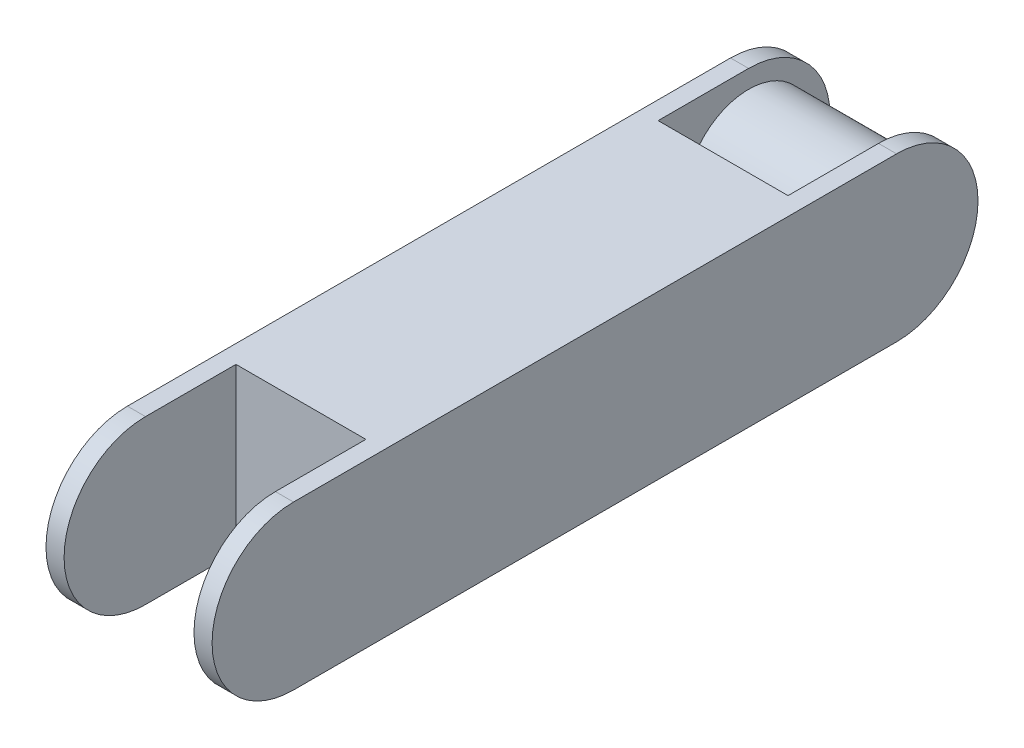
SolidWorks part; units mm, degrees
ref_plane "Piano frontale" through (0, 0, 0) normal (0, 0, 1) x (1, 0, 0)
ref_plane "Piano superiore" through (0, 0, 0) normal (0, 1, 0) x (1, 0, 0)
ref_plane "Piano destro" through (0, 0, 0) normal (1, 0, 0) x (0, 0, -1)
sketch "Schizzo1" plane through (0, 0, 0) normal (1, 0, 0) x (0, 0, -1)
  circle A0 centre (0, 0) radius 10.5
  dimension "D1" = 21
extrude "Estrusione-Estrusione1" add sketch "Schizzo1" along normal mid plane 21.54
ref_plane "Piano1" through (0, 0, 50) normal (0, 0, 1) x (1, 0, 0)
sketch "Schizzo3" plane through (0, 0, 0) normal (1, 0, 0) x (0, 0, -1)
  line L0 (-50, -14.5808) -> (-50, 15.0229) construction
  line L1 (-100, 13.5) -> (0, 13.5)
  line L2 (-100, -13.5) -> (0, -13.5)
  arc A1 (-100, -13.5) -> (-100, 13.5) centre (-100, 0) cw
  circle A2 centre (0, 0) radius 13.5
  arc A3 (0, -13.5) -> (0, 13.5) centre (0, 0) ccw
  dimension "D1" = 50
  dimension "D2" = 3
extrude "Estrusione-Estrusione2" add sketch "Schizzo3" along normal blind 3 from surface at 10.77 starting at face at (10.77, 0, -10.5)
mirror "Specchia4" about plane through (0, 0, 0) normal (1, 0, 0) of "Estrusione-Estrusione2"
sketch "Schizzo4" plane through (13.77, 0, 0) normal (1, 0, 0) x (0, 0, -1)
  line L0 (0, -13.5) -> (-100, -13.5) construction
  line L1 (-15, -13.5) -> (-85, -13.5)
  line L2 (-15, -13.5) -> (-15, 13.5)
  line L3 (-15, 13.5) -> (-85, 13.5)
  line L4 (-85, -13.5) -> (-85, 13.5)
  line L5 (-100, 13.5) -> (0, 13.5) construction
  arc A0 (-100, 13.5) -> (-100, -13.5) centre (-100, 0) ccw construction
  dimension "D1" = 15
  dimension "D2" = 15
extrude "Estrusione-Estrusione3" add sketch "Schizzo4" against normal up to next (24.54 mm away) from surface at -3 starting at face at (10.77, 0, -10.5)
